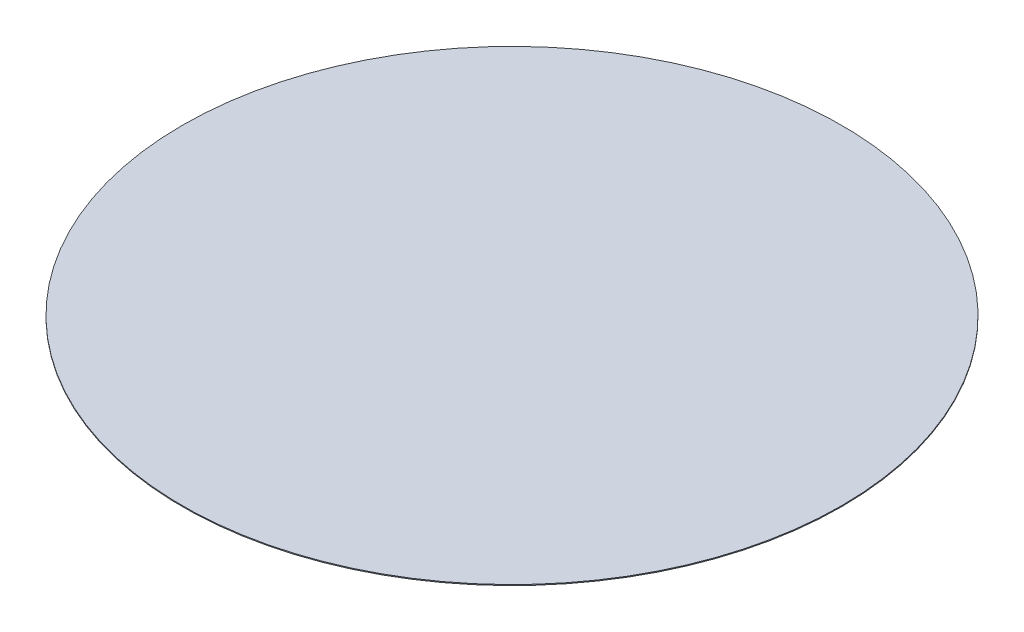
SolidWorks part; units mm, degrees
ref_plane "Front Plane" through (0, 0, 0) normal (0, 0, 1) x (1, 0, 0)
ref_plane "Top Plane" through (0, 0, 0) normal (0, 1, 0) x (1, 0, 0)
ref_plane "Right Plane" through (0, 0, 0) normal (1, 0, 0) x (0, 0, -1)
sketch "Sketch1" plane through (0, -1360, 0) normal (0, -1, 0) x (1, 0, 0)
  circle A2 centre (0, 0) radius 360
  circle A3 centre (0, 0) radius 360
  dimension "D1" = 10
extrude "Boss-Extrude1" add sketch "Sketch1" along normal blind 1
